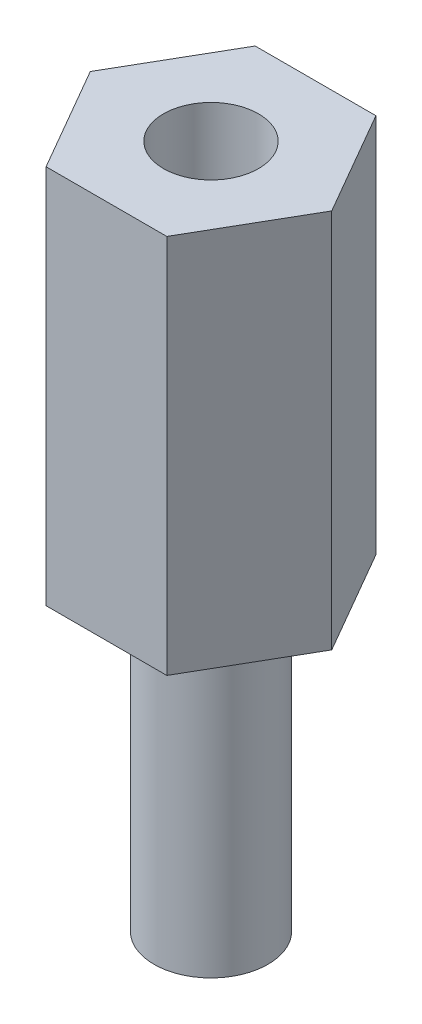
SolidWorks part; units mm, degrees
material "PVC Rigid"
ref_plane "Front Plane" through (0, 0, 0) normal (0, 0, 1) x (1, 0, 0)
ref_plane "Top Plane" through (0, 0, 0) normal (0, 1, 0) x (1, 0, 0)
ref_plane "Right Plane" through (0, 0, 0) normal (1, 0, 0) x (0, 0, -1)
sketch "Sketch1" plane through (0, 0, 0) normal (0, 1, 0) x (1, 0, 0)
  line L1 (3.1754, 0) -> (1.5877, 2.75)
  line L2 (1.5877, 2.75) -> (-1.5877, 2.75)
  line L3 (-1.5877, 2.75) -> (-3.1754, 0)
  line L4 (-3.1754, 0) -> (-1.5877, -2.75)
  line L5 (-1.5877, -2.75) -> (1.5877, -2.75)
  line L6 (1.5877, -2.75) -> (3.1754, 0)
  circle A0 centre (0, 0) radius 2.75 construction
  dimension "D1" = 5.5
extrude "Boss-Extrude1" add sketch "Sketch1" along normal mid plane 10
hole_wizard "M3 Tapped Hole1" positions "Sketch2" profile "Sketch4" tap size "M3" standard "ISO"
sketch "Sketch2" plane through (0, 5, 0) normal (0, 1, 0) x (1, 0, 0)
  point P0 (0, 0)
sketch "Sketch4" plane through (0, 5, 0) normal (1, 0, 0) x (0, 0, 1)
  line L0 (0, 0) -> (0, 5.7501)
  line L1 (0, 5.7501) -> (1.25, 4.999)
  line L2 (1.25, 4.999) -> (1.25, 0)
  line L5 (1.25, 0) -> (0, 0)
  line L10 (0, 5.7501) -> (-1.25, 4.999) construction
  line L11 (0, -6.35) -> (0, 107.95) construction
  dimension "Tap Drill Dia." = 2.5
  dimension "Tap Drill Depth" = 4.999
  dimension "Drill Angle" = 118
cosmetic thread "Hole Thread1" parameters "D1"=6, "D2"=3
sketch "Sketch7" plane through (0, -5, 0) normal (0, -1, 0) x (1, 0, 0)
  circle A0 centre (0, 0) radius 1.5
  dimension "D1" = 3
extrude "Boss-Extrude2" add sketch "Sketch7" along normal blind 8
